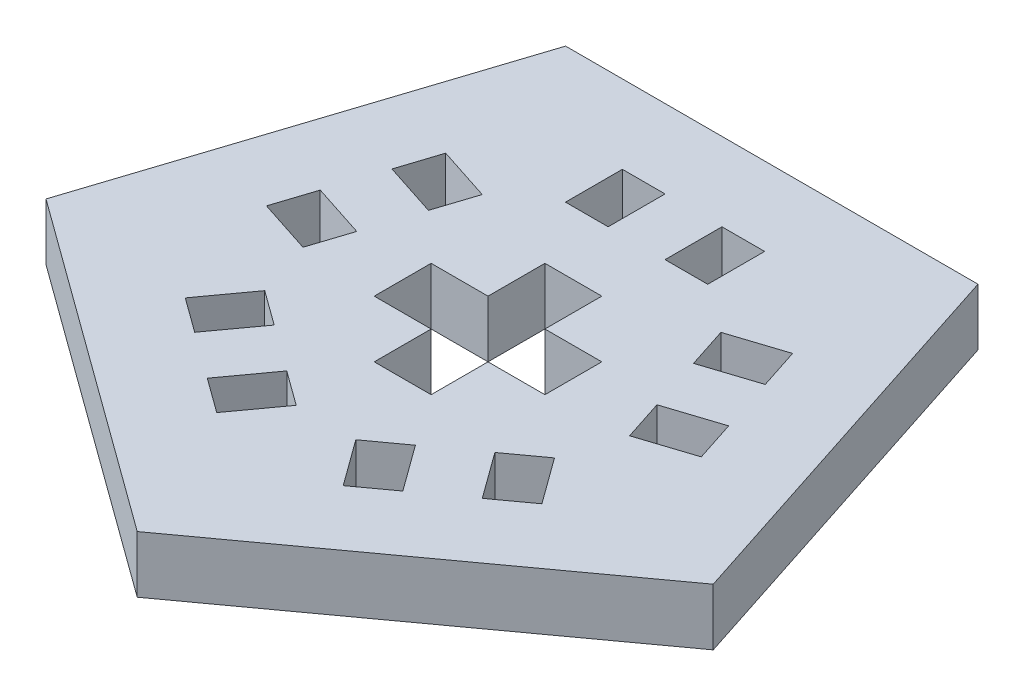
SolidWorks part; units mm, degrees
ref_plane "Front Plane" through (0, 0, 0) normal (0, 0, 1) x (1, 0, 0)
ref_plane "Top Plane" through (0, 0, 0) normal (0, 1, 0) x (1, 0, 0)
ref_plane "Right Plane" through (0, 0, 0) normal (1, 0, 0) x (0, 0, -1)
sketch "Sketch1" plane through (0, 0, 0) normal (0, 1, 0) x (1, 0, 0)
  line L0 (-2.9959, 18.9387) -> (-2.9959, -37.7212) construction
  line L1 (-2.9959, -37.7212) -> (26.792, -16.079)
  line L2 (26.792, -16.079) -> (15.414, 18.9387)
  line L3 (15.414, 18.9387) -> (-21.4058, 18.9387)
  line L4 (-21.4058, 18.9387) -> (-32.7838, -16.079)
  line L5 (-32.7838, -16.079) -> (-2.9959, -37.7212)
  line L6 (-2.9959, -29.0786) -> (18.5724, -13.4083) construction
  line L7 (18.5724, -13.4083) -> (10.334, 11.9467) construction
  line L8 (10.334, 11.9467) -> (-16.3258, 11.9467) construction
  line L9 (-16.3258, 11.9467) -> (-24.5642, -13.4083) construction
  line L10 (-24.5642, -13.4083) -> (-2.9959, -29.0786) construction
  line L11 (-42.7769, -6.4003) -> (64.8407, -6.4003) construction
  line L12 (15.2381, -3.1465) -> (16.4154, -6.77)
  line L13 (-0.4559, 11.9467) -> (3.3541, 11.9467)
  line L14 (-0.4559, 11.9467) -> (-0.4559, 6.8667)
  line L15 (-0.4559, 6.8667) -> (3.3541, 6.8667)
  line L16 (3.3541, 11.9467) -> (3.3541, 6.8667)
  line L17 (-5.5359, 11.9467) -> (-9.3459, 11.9467)
  line L18 (-5.5359, 11.9467) -> (-5.5359, 6.8667)
  line L19 (-5.5359, 6.8667) -> (-9.3459, 6.8667)
  line L20 (-9.3459, 11.9467) -> (-9.3459, 6.8667)
  line L21 (15.2381, -3.1465) -> (10.4067, -4.7163)
  line L22 (10.4067, -4.7163) -> (11.5841, -8.3398)
  line L23 (16.4154, -6.77) -> (11.5841, -8.3398)
  line L24 (13.6683, 1.6849) -> (12.4909, 5.3084)
  line L25 (13.6683, 1.6849) -> (8.8369, 0.1151)
  line L26 (8.8369, 0.1151) -> (7.6596, 3.7386)
  line L27 (12.4909, 5.3084) -> (7.6596, 3.7386)
  line L28 (5.7333, -22.7364) -> (2.651, -24.9759)
  line L29 (5.7333, -22.7364) -> (2.7474, -18.6266)
  line L30 (2.7474, -18.6266) -> (-0.335, -20.8661)
  line L31 (2.651, -24.9759) -> (-0.335, -20.8661)
  line L32 (9.8431, -19.7505) -> (12.9255, -17.511)
  line L33 (9.8431, -19.7505) -> (6.8572, -15.6406)
  line L34 (6.8572, -15.6406) -> (9.9395, -13.4012)
  line L35 (12.9255, -17.511) -> (9.9395, -13.4012)
  line L36 (-15.8349, -19.7505) -> (-18.9173, -17.511)
  line L37 (-15.8349, -19.7505) -> (-12.849, -15.6406)
  line L38 (-12.849, -15.6406) -> (-15.9313, -13.4012)
  line L39 (-18.9173, -17.511) -> (-15.9313, -13.4012)
  line L40 (-11.7251, -22.7364) -> (-8.6428, -24.9759)
  line L41 (-11.7251, -22.7364) -> (-8.7392, -18.6266)
  line L42 (-8.7392, -18.6266) -> (-5.6568, -20.8661)
  line L43 (-8.6428, -24.9759) -> (-5.6568, -20.8661)
  line L44 (-19.6601, 1.6849) -> (-18.4827, 5.3084)
  line L45 (-19.6601, 1.6849) -> (-14.8287, 0.1151)
  line L46 (-14.8287, 0.1151) -> (-13.6514, 3.7386)
  line L47 (-18.4827, 5.3084) -> (-13.6514, 3.7386)
  line L48 (-21.2299, -3.1465) -> (-22.4073, -6.77)
  line L49 (-21.2299, -3.1465) -> (-16.3985, -4.7163)
  line L50 (-16.3985, -4.7163) -> (-17.5759, -8.3398)
  line L51 (-22.4073, -6.77) -> (-17.5759, -8.3398)
  circle A0 centre (-2.9959, -6.4003) radius 25.3391 construction
  circle A1 centre (-2.9959, -6.4003) radius 18.3471 construction
  point P59 (-2.9959, -6.4003)
  dimension "D1" = 36.8198
  dimension "D2" = 26.6598
  dimension "D3" = 5.08
  dimension "D4" = 3.81
  dimension "D5" = 2.54
  dimension "D6" = 2.54
  dimension "D7" = 3.81
  dimension "D8" = 5.08
  dimension "D9" = 5
extrude "Boss-Extrude1" add sketch "Sketch1" along normal blind 5.08
sketch "Sketch2" plane through (0, 5.08, 0) normal (0, 1, 0) x (1, 0, 0)
  line L0 (-2.9959, 18.9387) -> (-2.9959, -37.7212) construction
  line L1 (15.414, 18.9387) -> (-21.4058, 18.9387) construction
  line L2 (-2.9959, -37.7212) -> (26.792, -16.079) construction
  line L3 (-27.0948, 1.4299) -> (26.792, -16.079) construction
  line L4 (-21.4058, 18.9387) -> (-32.7838, -16.079) construction
  line L5 (21.103, 1.4299) -> (-32.7838, -16.079) construction
  line L6 (26.792, -16.079) -> (15.414, 18.9387) construction
  line L7 (-43.8744, -6.4003) -> (57.3486, -6.4003) construction
  line L8 (-2.9959, 1.2197) -> (-0.4559, 1.2197)
  line L9 (-0.4559, 1.2197) -> (-0.4559, -3.8603)
  line L10 (-0.4559, -3.8603) -> (4.6241, -3.8603)
  line L11 (4.6241, -3.8603) -> (4.6241, -6.4003)
  line L12 (4.6241, -6.4003) -> (4.6241, -8.9403)
  line L13 (4.6241, -8.9403) -> (-0.4559, -8.9403)
  line L14 (-0.4559, -8.9403) -> (-0.4559, -14.0203)
  line L15 (-0.4559, -14.0203) -> (-2.9959, -14.0203)
  line L16 (-2.9959, -14.0203) -> (-5.5359, -14.0203)
  line L17 (-5.5359, -14.0203) -> (-5.5359, -8.9403)
  line L18 (-5.5359, -8.9403) -> (-10.6159, -8.9403)
  line L19 (-10.6159, -8.9403) -> (-10.6159, -6.4003)
  line L20 (-10.6159, -6.4003) -> (-10.6159, -3.8603)
  line L21 (-10.6159, -3.8603) -> (-5.5359, -3.8603)
  line L22 (-5.5359, -3.8603) -> (-5.5359, 1.2197)
  line L23 (-5.5359, 1.2197) -> (-2.9959, 1.2197)
  point P16 (-2.9959, -6.4003)
  point P42 (-2.9959, -6.4003)
  dimension "D1" = 2.54
  dimension "D2" = 5.08
  dimension "D3" = 5.08
  dimension "D4" = 2.54
  dimension "D5" = 4
extrude "Cut-Extrude1" cut sketch "Sketch2" against normal blind 5.08
